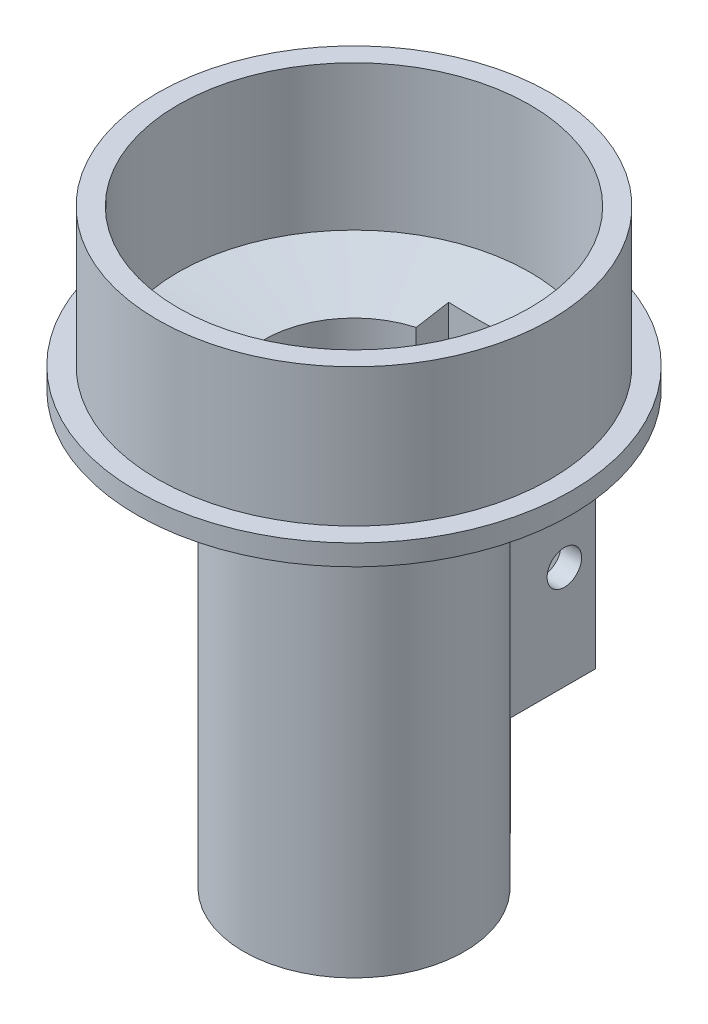
SolidWorks part; units mm, degrees
material "PET"
ref_plane "Alzado" through (0, 0, 0) normal (0, 0, 1) x (1, 0, 0)
ref_plane "Planta" through (0, 0, 0) normal (0, 1, 0) x (1, 0, 0)
ref_plane "Vista lateral" through (0, 0, 0) normal (1, 0, 0) x (0, 0, -1)
sketch "Croquis1" plane through (0, 0, 0) normal (1, 0, 0) x (0, 0, -1)
  line L0 (0, 0) -> (0, 141.574) construction
  line L1 (28.5, 149.2566) -> (28.5, 129.2566)
  line L2 (28.5, 129.2566) -> (31.5, 129.2566)
  line L3 (31.5, 129.2566) -> (31.5, 126.2566)
  line L4 (25.5, 149.2566) -> (25.5, 128.2449)
  line L5 (16, 123.5235) -> (16, 63.6685)
  line L6 (31.5, 126.2566) -> (16, 123.5235)
  line L7 (25.5, 128.2449) -> (25.5, 128.2449)
  line L8 (25.5, 128.2449) -> (25.5, 128.2449)
  line L9 (25.5, 128.2449) -> (13, 126.0408)
  line L10 (13, 126.0408) -> (13, 63.6685)
  line L11 (25.5, 149.2566) -> (28.5, 149.2566)
  line L12 (13, 63.6685) -> (16, 63.6685)
  dimension "D1" = 31.5
  dimension "D2" = 3
  dimension "D3" = 16
  dimension "D4" = 3
  dimension "D5" = 20
  dimension "D6" = 100
  dimension "D7" = 3
revolve "Revolución1" add sketch "Croquis1" angle 360 about L0
ref_plane "Plano1" through (0, 83.6685, 0) normal (0, -1, 0) x (-1, 0, 0)
sketch "Croquis2" plane through (0, 83.6685, 0) normal (0, -1, 0) x (-1, 0, 0)
  line L0 (0, 0) -> (0, 30.3568) construction
  line L1 (-10, 25) -> (10, 25)
  line L2 (-10, 25) -> (-10, 16)
  line L3 (-10, 16) -> (10, 16)
  line L4 (10, 25) -> (10, 16)
  circle A0 centre (0, 0) radius 16 construction
  dimension "D1" = 20
  dimension "D2" = 9
extrude "Saliente-Extruir1" add sketch "Croquis2" against normal blind 30 separate body
sketch "Croquis3" plane through (10, 0, 0) normal (1, 0, 0) x (0, 0, -1)
  line L0 (20.5, 113.6685) -> (20.5, 83.6685) construction
  line L1 (25, 113.6685) -> (16, 113.6685) construction
  line L2 (25, 83.6685) -> (16, 83.6685) construction
  line L3 (16, 98.6685) -> (25, 98.6685) construction
  line L4 (16, 113.6685) -> (16, 83.6685) construction
  line L5 (25, 113.6685) -> (25, 83.6685) construction
  circle A0 centre (20.5, 98.6685) radius 2.5
  dimension "D1" = 5
extrude "Cortar-Extruir1" cut sketch "Croquis3" against normal blind 30
sketch "Croquis4" plane through (0, 0, -16) normal (0, 0, 1) x (1, 0, 0)
  line L1 (-10, 113.6685) -> (10, 113.6685)
  line L2 (-10, 113.6685) -> (-10, 83.6685)
  line L3 (-10, 83.6685) -> (10, 83.6685)
  line L4 (10, 113.6685) -> (10, 83.6685)
extrude "Saliente-Extruir2" add sketch "Croquis4" along normal up to surface (3.51 mm away)
ref_plane "Plano2" through (0, 0, -12.49) normal (0, 0, -1) x (-1, 0, 0)
sketch "Croquis5" plane through (0, 0, -12.49) normal (0, 0, -1) x (-1, 0, 0)
  line L15 (-7, 110.6685) -> (-7, 86.6685)
  line L16 (-7, 86.6685) -> (7, 86.6685)
  line L17 (7, 86.6685) -> (7, 110.6685)
  line L18 (7, 110.6685) -> (-7, 110.6685)
  line L19 (-7, 110.6685) -> (-7, 86.6685)
  line L20 (-7, 86.6685) -> (7, 86.6685)
  line L21 (7, 86.6685) -> (7, 110.6685)
  line L22 (7, 110.6685) -> (-7, 110.6685)
  dimension "D1" = 3
extrude "Cortar-Extruir2" cut sketch "Croquis5" along normal offset from surface (11.01 mm away) 1.5 up to face at (0, 98.6685, -25)
sketch "Croquis6" plane through (0, 63.6685, 0) normal (0, -1, 0) x (1, 0, 0)
  line L0 (0, 0) -> (0, -23.7651) construction
  line L1 (-4.5, -18.2277) -> (4.5, -18.2277)
  line L2 (-4.5, -18.2277) -> (-4.5, -15.3542)
  line L3 (-4.5, -15.3542) -> (4.5, -15.3542)
  line L4 (4.5, -18.2277) -> (4.5, -15.3542)
  circle A0 centre (0, 0) radius 16 construction
  circle A1 centre (0, 0) radius 16
  circle M7 centre (0, 0) radius 16
  dimension "D1" = 9
extrude "Saliente-Extruir3" add sketch "Croquis6" against normal up to surface (60.3443 mm away) contours L0 L2 L1 M7 | A1 L0 L1 L4
sketch "Croquis7" plane through (0, 63.6685, 0) normal (0, -1, 0) x (1, 0, 0)
  line L9 (3.5, -15.3542) -> (3.5, -17.2277)
  line L10 (3.5, -17.2277) -> (-3.5, -17.2277)
  line L11 (-3.5, -17.2277) -> (-3.5, -15.3542)
  line L12 (3.5, -12.52) -> (3.5, -17.2277)
  line L13 (3.5, -17.2277) -> (-3.5, -17.2277)
  line L14 (-3.5, -17.2277) -> (-3.5, -12.52)
  circle A0 centre (0, 0) radius 13 construction
  circle A1 centre (0, 0) radius 13
  circle M8 centre (0, 0) radius 13
  dimension "D1" = 1
extrude "Cortar-Extruir3" cut sketch "Croquis7" against normal up to surface (62.3723 mm away) contours L14 L13 L12 M8 up to face at (0, 126.0408, -13)
